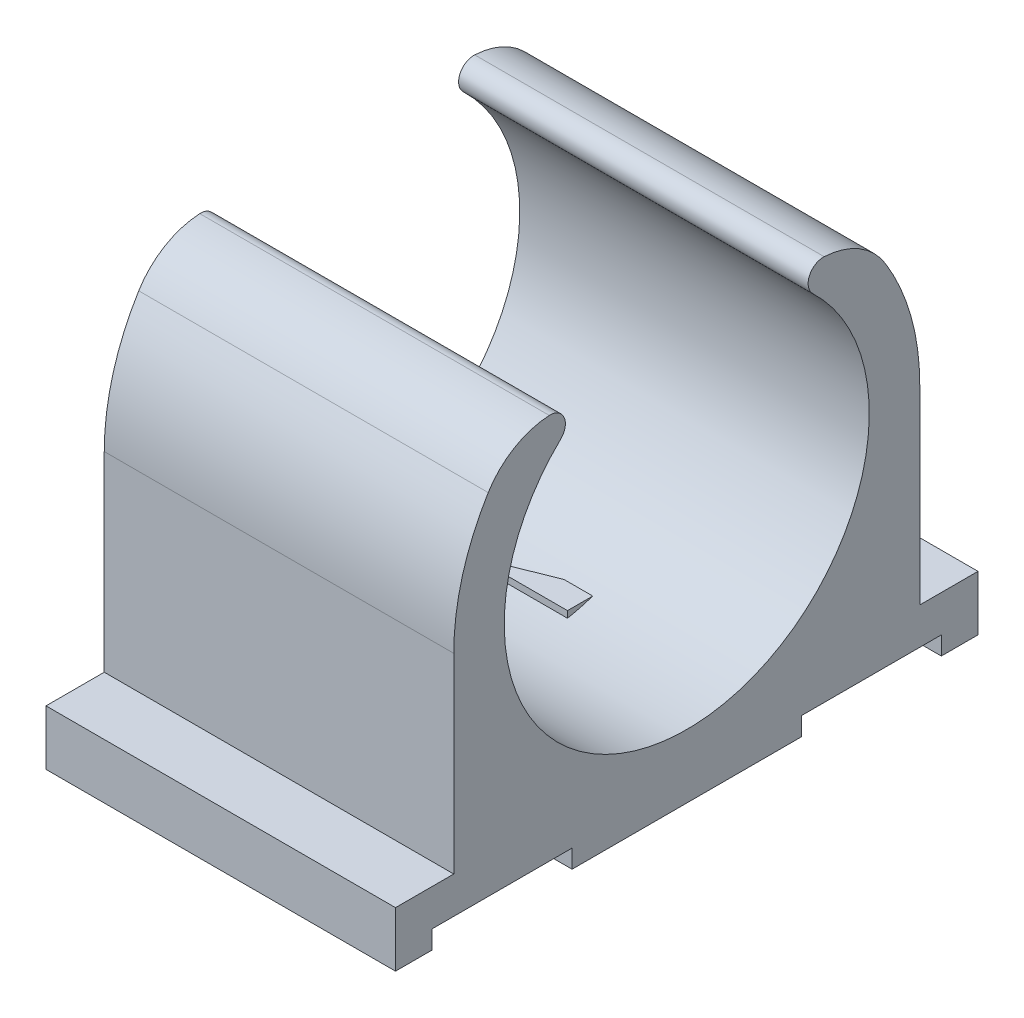
SolidWorks part; units mm, degrees
ref_plane "Front" through (0, 0, 0) normal (0, 0, 1) x (1, 0, 0)
ref_plane "Top" through (0, 0, 0) normal (0, 1, 0) x (1, 0, 0)
ref_plane "Right" through (0, 0, 0) normal (1, 0, 0) x (0, 0, -1)
sketch "Sketch1" plane through (0, 0, 0) normal (0, 1, 0) x (1, 0, 0)
  line L1 (-11.43, 19.05) -> (11.43, 19.05)
  line L2 (-11.43, 19.05) -> (-11.43, -19.05)
  line L3 (-11.43, -19.05) -> (11.43, -19.05)
  line L4 (11.43, 19.05) -> (11.43, -19.05)
  line L5 (-11.43, 19.05) -> (11.43, -19.05) construction
  line L6 (-11.43, -19.05) -> (11.43, 19.05) construction
  point P0 (0, 0)
  dimension "D1" = 38.1
  dimension "D2" = 22.86
extrude "Boss-Extrude1" add sketch "Sketch1" along normal blind 2.4
sketch "Sketch2" plane through (0, 0, 0) normal (0, -1, 0) x (1, 0, 0)
  line L0 (-11.43, -19.05) -> (-11.43, 19.05) construction
  line L1 (11.43, 7.5) -> (-11.43, 7.5)
  line L2 (11.43, 7.5) -> (11.43, -7.5)
  line L3 (11.43, -7.5) -> (-11.43, -7.5)
  line L4 (-11.43, 7.5) -> (-11.43, -7.5)
  line L5 (11.43, 7.5) -> (-11.43, -7.5) construction
  line L6 (11.43, -7.5) -> (-11.43, 7.5) construction
  line L8 (11.43, -19.05) -> (-11.43, -19.05)
  line L9 (11.43, -19.05) -> (11.43, -16.65)
  line L10 (11.43, -16.65) -> (-11.43, -16.65)
  line L11 (-11.43, -19.05) -> (-11.43, -16.65)
  line L12 (11.43, -19.05) -> (-11.43, -16.65) construction
  line L13 (11.43, -16.65) -> (-11.43, -19.05) construction
  line L14 (11.43, 19.05) -> (-11.43, 19.05)
  line L15 (11.43, 19.05) -> (11.43, 16.65)
  line L16 (11.43, 16.65) -> (-11.43, 16.65)
  line L17 (-11.43, 19.05) -> (-11.43, 16.65)
  line L18 (11.43, 19.05) -> (-11.43, 16.65) construction
  line L19 (11.43, 16.65) -> (-11.43, 19.05) construction
  point P0 (0, 0)
  point P12 (0, -17.85)
  point P18 (0, 17.85)
  dimension "D1" = 2.4
  dimension "D2" = 2.4
  dimension "D3" = 15
extrude "Boss-Extrude2" add sketch "Sketch2" along normal blind 1.2
sketch "Sketch3" plane through (0, -1.2, 0) normal (0, -1, 0) x (1, 0, 0)
  line L0 (11.43, 7.5) -> (-11.43, 7.5) construction
  line L1 (-7.5, -7.5) -> (7.5, -7.5)
  line L2 (-7.5, -7.5) -> (-7.5, 7.5)
  line L3 (-7.5, 7.5) -> (7.5, 7.5)
  line L4 (7.5, -7.5) -> (7.5, 7.5)
  line L5 (-7.5, -7.5) -> (7.5, 7.5) construction
  line L6 (-7.5, 7.5) -> (7.5, -7.5) construction
  point P0 (0, 0)
  dimension "D1" = 15
extrude "Boss-Extrude3" add sketch "Sketch3" along normal blind 2
sketch "Sketch4" plane through (0, 2.4, 0) normal (0, 1, 0) x (1, 0, 0)
  line L0 (11.43, -19.05) -> (11.43, 19.05) construction
  line L1 (-11.43, -15.24) -> (11.43, -15.24)
  line L2 (-11.43, -15.24) -> (-11.43, 15.24)
  line L3 (-11.43, 15.24) -> (11.43, 15.24)
  line L4 (11.43, -15.24) -> (11.43, 15.24)
  line L5 (-11.43, -15.24) -> (11.43, 15.24) construction
  line L6 (-11.43, 15.24) -> (11.43, -15.24) construction
  point P0 (0, 0)
  dimension "D1" = 30.48
extrude "Boss-Extrude4" add sketch "Sketch4" along normal blind 22.86
sketch "Sketch5" plane through (11.43, 0, 0) normal (1, 0, 0) x (0, 0, -1)
  line L0 (-19.05, 2.4) -> (-15.24, 2.4) construction
  circle A0 centre (0, 14.9) radius 11.938
  point P4 (0, 0)
  dimension "D1" = 23.876
  dimension "D2" = 12.5
extrude "Cut-Extrude1" cut sketch "Sketch5" against normal through all
sketch "Sketch6" plane through (11.43, 0, 0) normal (1, 0, 0) x (0, 0, -1)
  line L0 (-15.24, 25.26) -> (-15.24, 2.4) construction
  line L1 (-15.24, 25.26) -> (-11.1771, 25.26)
  line L2 (-15.24, 25.26) -> (-5.9318, 25.26) construction
  line L3 (-15.24, 14.9) -> (-15.24, 25.26)
  line L4 (15.24, 14.9) -> (15.24, 25.26)
  line L5 (15.24, 25.26) -> (11.1771, 25.26)
  line L6 (5.9318, 25.26) -> (15.24, 25.26) construction
  arc A0 (15.24, 14.9) -> (11.1771, 25.26) centre (0, 14.9) ccw
  arc A1 (-5.9318, 25.26) -> (5.9318, 25.26) centre (0, 14.9) ccw construction
  arc A2 (-11.1771, 25.26) -> (-15.24, 14.9) centre (0, 14.9) ccw
  point P19 (0, 0)
extrude "Cut-Extrude2" cut sketch "Sketch6" against normal through all
fillet "Fillet1" radius 5 2 edges at (0, 25.26, -11.1771) (0, 25.26, 11.1771)
fillet "Fillet2" radius 1 2 edges at (0, 25.26, 5.9318) (0, 25.26, -5.9318)
sketch "Sketch7" plane through (0, 2.4, 0) normal (0, 1, 0) x (1, 0, 0)
  line L0 (-4.57, 2.2) -> (1.43, 2.2)
  line L1 (1.43, 2.2) -> (1.43, 4.6)
  line L2 (1.43, 4.6) -> (-4.57, 2.2)
  line L3 (7.4546, 0) -> (-4.5181, 0) construction
  line L4 (1.43, -4.6) -> (-4.57, -2.2)
  line L5 (1.43, -2.2) -> (1.43, -4.6)
  line L6 (-4.57, -2.2) -> (1.43, -2.2)
  line L7 (11.43, -11.938) -> (11.43, 11.938) construction
  point P6 (11.3129, 0)
  point P7 (-4.5181, 0)
  point P8 (7.4546, 0)
  dimension "D1" = 2.2
  dimension "D2" = 2.4
  dimension "D3" = 6
  dimension "D4" = 10
extrude "Boss-Extrude5" add sketch "Sketch7" along normal blind 1.2
